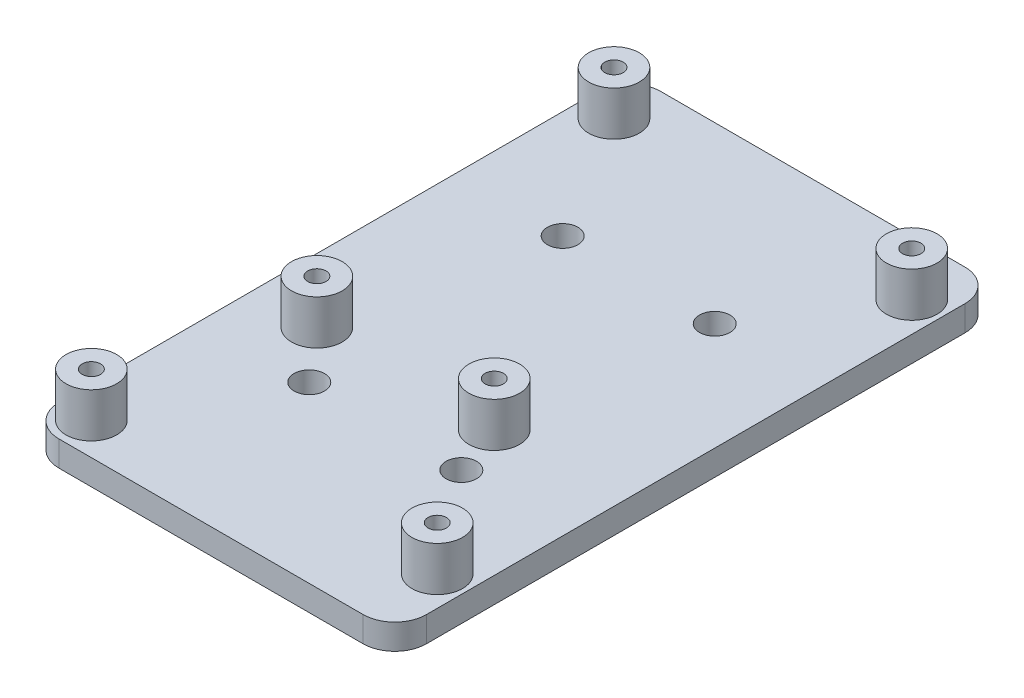
SolidWorks part; units mm, degrees
ref_plane "Front Plane" through (0, 0, 0) normal (0, 0, 1) x (1, 0, 0)
ref_plane "Top Plane" through (0, 0, 0) normal (0, 1, 0) x (1, 0, 0)
ref_plane "Right Plane" through (0, 0, 0) normal (1, 0, 0) x (0, 0, -1)
sketch "Sketch1" plane through (0, 0, 0) normal (0, 1, 0) x (1, 0, 0)
  line L1 (-29, 47.5) -> (29, 47.5)
  line L2 (-29, 47.5) -> (-29, -47.5)
  line L3 (-29, -47.5) -> (29, -47.5)
  line L4 (29, 47.5) -> (29, -47.5)
  line L5 (-29, 47.5) -> (29, -47.5) construction
  line L6 (-29, -47.5) -> (29, 47.5) construction
  point P0 (0, 0)
  dimension "D1" = 58
  dimension "D2" = 95
extrude "Boss-Extrude1" add sketch "Sketch1" along normal blind 4
sketch "Sketch2" plane through (0, 4, 0) normal (0, 1, 0) x (1, 0, 0)
  line L0 (-2.2, 0) -> (2.2, 0) construction
  line L1 (0, -2.2) -> (0, 2.2) construction
  circle A0 centre (-24, 40.1) radius 4
  circle A1 centre (24.25, 38.85) radius 4
  circle A2 centre (-18.9, -11.9) radius 4
  circle A3 centre (9.1, -11.9) radius 4
  circle A4 centre (-24, -42.4) radius 4
  circle A5 centre (24.3, -36.1) radius 4
  circle A6 centre (-24, 40.1) radius 1.45
  circle A7 centre (24.25, 38.85) radius 1.45
  circle A8 centre (9.1, -11.9) radius 1.45
  circle A9 centre (24.3, -36.1) radius 1.45
  circle A10 centre (-18.9, -11.9) radius 1.45
  circle A11 centre (-24, -42.4) radius 1.45
  dimension "D1" = 8
  dimension "D2" = 8
  dimension "D3" = 8
  dimension "D4" = 8
  dimension "D5" = 8
  dimension "D6" = 8
  dimension "D19" = 2.9
  dimension "D20" = 2.9
  dimension "D21" = 2.9
  dimension "D22" = 2.9
  dimension "D23" = 2.9
  dimension "D24" = 2.9
  dimension "D7" = 11.9
  dimension "D8" = 11.9
  dimension "D9" = 42.4
  dimension "D10" = 36.1
  dimension "D11" = 40.1
  dimension "D12" = 38.85
  dimension "D13" = 24.25
  dimension "D14" = 24
  dimension "D15" = 18.9
  dimension "D16" = 9.1
  dimension "D17" = 24
  dimension "D18" = 24.3
extrude "Boss-Extrude2" add sketch "Sketch2" along normal blind 7
fillet "Fillet1" radius 5 4 edges at (29, 2, 47.5) (-29, 2, 47.5) (-29, 2, -47.5) (29, 2, -47.5)
sketch "Sketch3" plane through (0, 0, 0) normal (0, 1, 0) x (1, 0, 0)
  line L0 (0, -6.05) -> (0, 6.05) construction
  line L1 (-6.05, 0) -> (6.05, 0) construction
  circle A0 centre (-12, 20) radius 2.4
  circle A1 centre (12, 20) radius 2.4
  circle A2 centre (-12, -20) radius 2.4
  circle A3 centre (12, -20) radius 2.4
  dimension "D1" = 4.8
  dimension "D2" = 4.8
  dimension "D3" = 4.8
  dimension "D4" = 4.8
  dimension "D5" = 12
  dimension "D6" = 12
  dimension "D7" = 12
  dimension "D8" = 12
  dimension "D9" = 20
  dimension "D10" = 20
  dimension "D11" = 20
  dimension "D12" = 20
extrude "Cut-Extrude1" cut sketch "Sketch3" along normal up to next
